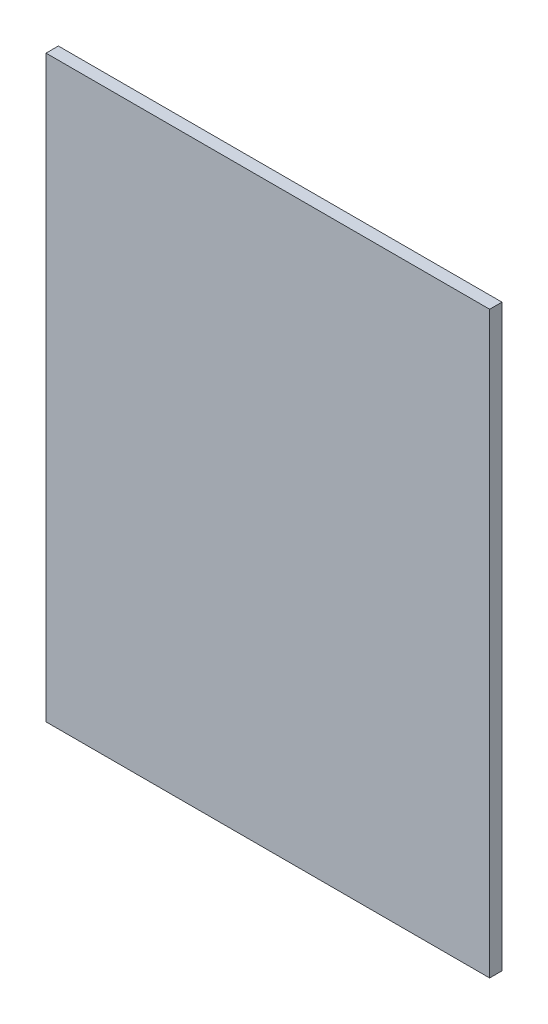
SolidWorks part; units mm, degrees
ref_plane "正面" through (0, 0, 0) normal (0, 0, 1) x (1, 0, 0)
ref_plane "平面" through (0, 0, 0) normal (0, 1, 0) x (1, 0, 0)
ref_plane "右側面" through (0, 0, 0) normal (1, 0, 0) x (0, 0, -1)
sketch "ｽｹｯﾁ1" plane through (0, 0, 0) normal (0, 0, 1) x (1, 0, 0)
  line L1 (0, 0) -> (36, 0)
  line L2 (0, 0) -> (0, 47)
  line L3 (0, 47) -> (36, 47)
  line L4 (36, 0) -> (36, 47)
extrude "ﾎﾞｽ - 押し出し1" add sketch "ｽｹｯﾁ1" along normal blind 1
